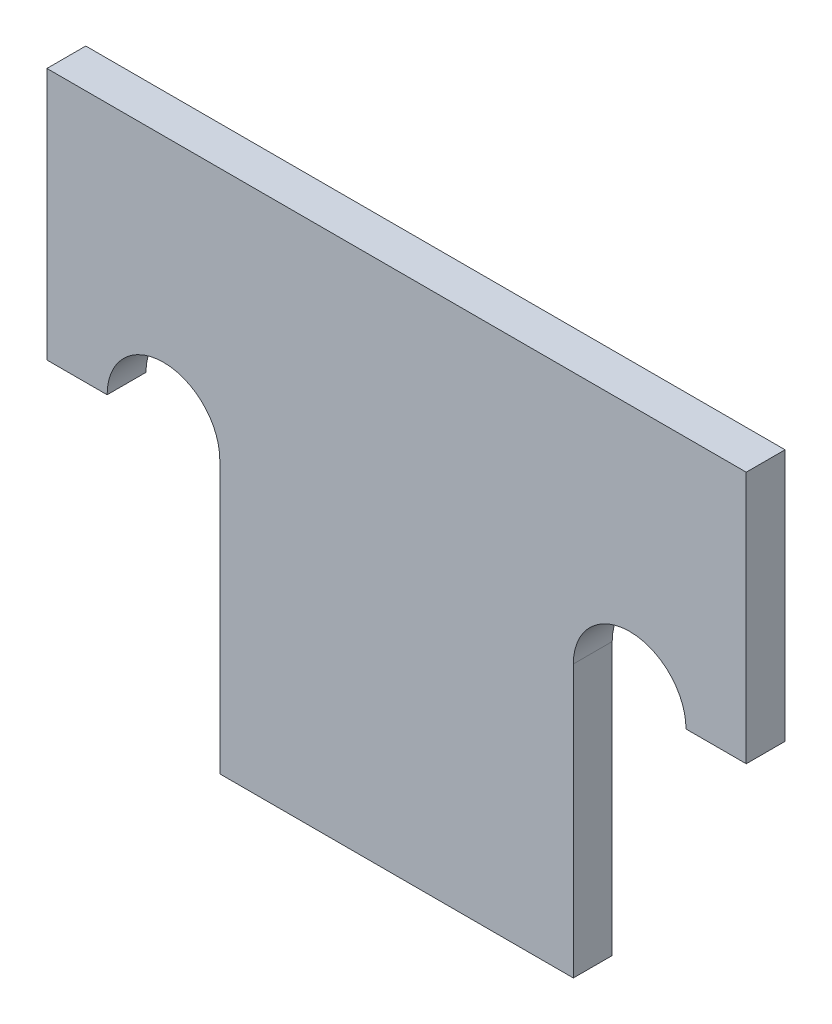
SolidWorks part; units mm, degrees
material "7075-T6 (SN)"
ref_plane "Front Plane" through (0, 0, 0) normal (0, 0, 1) x (1, 0, 0)
ref_plane "Top Plane" through (0, 0, 0) normal (0, 1, 0) x (1, 0, 0)
ref_plane "Right Plane" through (0, 0, 0) normal (1, 0, 0) x (0, 0, -1)
sketch "Sketch1" plane through (0, 0, 0) normal (0, 0, 1) x (1, 0, 0)
  line L0 (-22.86, 0.635) -> (22.86, 0.635) construction
  line L1 (-22.86, -17.145) -> (22.86, -17.145)
  line L2 (-22.86, -17.145) -> (-22.86, 17.145)
  line L3 (-22.86, 17.145) -> (22.86, 17.145)
  line L4 (22.86, -17.145) -> (22.86, 17.145)
  line L5 (-22.86, -17.145) -> (22.86, 17.145) construction
  line L6 (-22.86, 17.145) -> (22.86, -17.145) construction
  line L7 (0, 5.8923) -> (0, -3.1789) construction
  circle A0 centre (15.24, 0.635) radius 3.175
  circle A1 centre (-15.24, 0.635) radius 3.175
  point P0 (0, 0)
  dimension "D5" = 6.35
  dimension "D1" = 30.48
  dimension "D3" = 34.29
  dimension "D4" = 16.51
  dimension "D6" = 45.72
extrude "Boss-Extrude1" add sketch "Sketch1" along normal blind 2.54
sketch "Sketch2" plane through (0, 0, 0) normal (0, 0, 1) x (1, 0, 0)
  line L0 (0, -10.4784) -> (0, 10.4784) construction
  line L1 (11.557, 0.635) -> (11.557, -17.145)
  line L2 (-22.86, -17.145) -> (22.86, -17.145) construction
  line L4 (18.923, 0.635) -> (22.86, 0.635)
  line L6 (-11.557, 0.635) -> (-11.557, -17.145)
  line L20 (22.86, -17.145) -> (22.86, 17.145) construction
  line L22 (-18.923, 0.635) -> (-22.86, 0.635)
  line L23 (-22.86, 17.145) -> (-22.86, -17.145) construction
  line L24 (-22.86, 0.635) -> (-22.86, -17.145)
  line L25 (-22.86, -17.145) -> (-11.557, -17.145)
  line L26 (22.86, -17.145) -> (22.86, 0.635)
  line L27 (11.557, -17.145) -> (22.86, -17.145)
  arc A0 (18.923, 0.635) -> (11.557, 0.635) centre (15.24, 0.635) ccw
  circle A1 centre (15.24, 0.635) radius 3.175 construction
  arc A2 (-18.923, 0.635) -> (-11.557, 0.635) centre (-15.24, 0.635) cw
  dimension "D1" = 0.508
extrude "Cut-Extrude1" cut sketch "Sketch2" along normal up to surface (2.54 mm away) up to face at (0, 0, 2.54)
